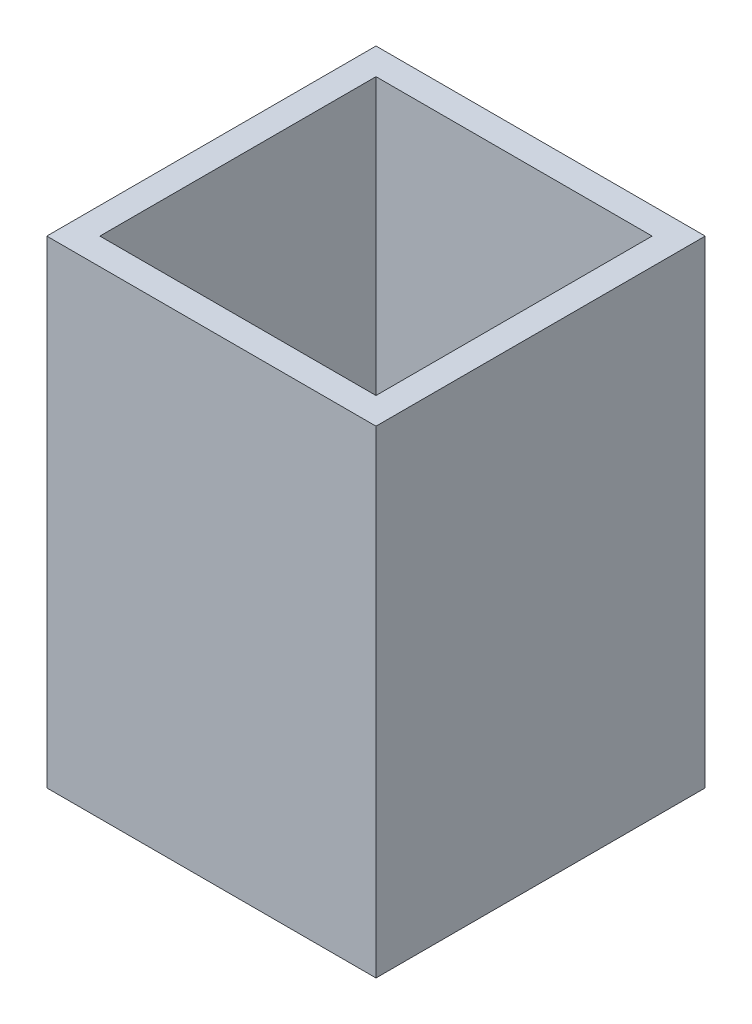
SolidWorks part; units mm, degrees
ref_plane "Front Plane" through (0, 0, 0) normal (0, 0, 1) x (1, 0, 0)
ref_plane "Top Plane" through (0, 0, 0) normal (0, 1, 0) x (1, 0, 0)
ref_plane "Right Plane" through (0, 0, 0) normal (1, 0, 0) x (0, 0, -1)
sketch "Sketch1" plane through (0, 0, 0) normal (0, 1, 0) x (1, 0, 0)
  line L1 (-13, 13) -> (13, 13)
  line L2 (-13, 13) -> (-13, -13)
  line L3 (-13, -13) -> (13, -13)
  line L4 (13, 13) -> (13, -13)
  line L5 (-13, 13) -> (13, -13) construction
  line L6 (-13, -13) -> (13, 13) construction
  line L7 (-15.5, -15.5) -> (15.5, -15.5)
  line L8 (-15.5, -15.5) -> (-15.5, 15.5)
  line L9 (-15.5, 15.5) -> (15.5, 15.5)
  line L10 (15.5, -15.5) -> (15.5, 15.5)
  line L11 (-15.5, -15.5) -> (15.5, 15.5) construction
  line L12 (-15.5, 15.5) -> (15.5, -15.5) construction
  point P0 (0, 0)
  point P6 (0, 0)
  dimension "D1" = 26
  dimension "D2" = 31
extrude "Boss-Extrude1" add sketch "Sketch1" against normal blind 45
sketch "Sketch3" plane through (0, 0, 15.5) normal (0, 0, 1) x (1, 0, 0)
  line L0 (0, -45) -> (0, -16.5787) construction
  line L1 (-15.5, -45) -> (15.5, -45) construction
  circle A0 centre (0, -16.8428) radius 5.255
